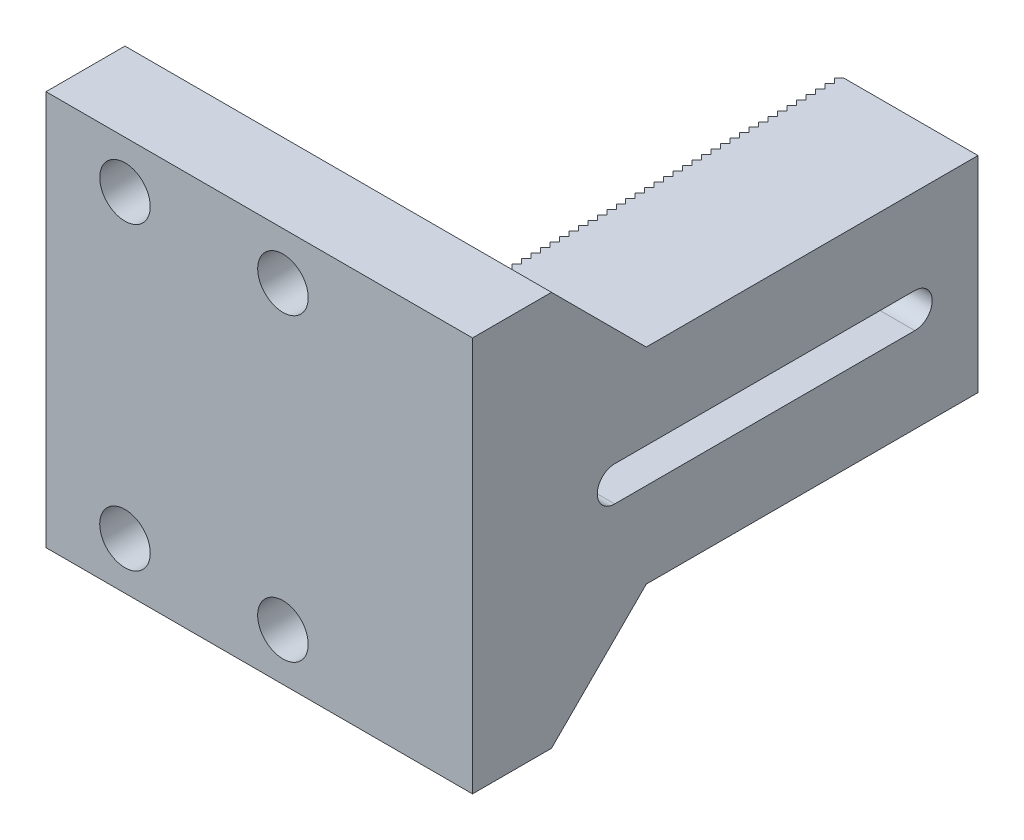
SolidWorks part; units mm, degrees
ref_plane "前视基准面" through (0, 0, 0) normal (0, 0, 1) x (1, 0, 0)
ref_plane "上视基准面" through (0, 0, 0) normal (0, 1, 0) x (1, 0, 0)
ref_plane "右视基准面" through (0, 0, 0) normal (1, 0, 0) x (0, 0, -1)
sketch "草图1" plane through (0, 0, 0) normal (0, 1, 0) x (1, 0, 0)
  line L0 (0, 0) -> (-27, 0)
  line L1 (-27, 0) -> (-27, 5)
  line L2 (-27, 5) -> (-8, 5)
  line L3 (-8, 5) -> (-8, 32)
  line L4 (-8, 32) -> (0, 32)
  line L5 (0, 32) -> (0, 0)
  dimension "D1" = 5
  dimension "D2" = 8
  dimension "D3" = 27
  dimension "D4" = 32
extrude "凸台-拉伸1" add sketch "草图1" along normal blind 25
sketch "草图4" plane through (0, 0, 0) normal (0, 0, 1) x (1, 0, 0)
  line L0 (-27, 25) -> (-8, 25) construction
  line L1 (-17, 27.5741) -> (-17, -6.7865) construction
  line L2 (-27, 12.5) -> (-8.9406, 12.5) construction
  line L3 (-27, 25) -> (-27, 0) construction
  line L5 (-8, 25) -> (-8, 0) construction
  circle A0 centre (-22, 22) radius 1.6
  circle A1 centre (-12, 22) radius 1.6
  circle A2 centre (-22, 3) radius 1.6
  circle A3 centre (-12, 3) radius 1.6
  dimension "D1" = 3.2
  dimension "D2" = 10
  dimension "D3" = 19
  dimension "D5" = 4
  dimension "D4" = 10
extrude "切除-拉伸2" cut sketch "草图4" along direction (0, 0, 1) on the side against the normal through all
sketch "草图8" plane through (-8, 0, 0) normal (-1, 0, 0) x (0, 0, 1)
  line L0 (-32, 19) -> (-11, 19)
  line L1 (-32, 25) -> (-32, 0) construction
  line L2 (-11, 19) -> (-5, 25)
  line L3 (-5, 25) -> (-32, 25)
  line L4 (-32, 25) -> (-32, 19)
  line L5 (-32, 12.5) -> (0.3903, 12.5) construction
  line L6 (-11, 6) -> (-5, 0)
  line L7 (-5, 0) -> (-32, 0)
  line L8 (-32, 0) -> (-32, 6)
  line L9 (-32, 6) -> (-11, 6)
  line L10 (-5, 25) -> (-5, 0) construction
  dimension "D1" = 45
  dimension "D2" = 13
extrude "切除-拉伸5" cut sketch "草图8" against normal through all
sketch "草图11" plane through (0, 6, 0) normal (0, -1, 0) x (1, 0, 0)
  line L0 (-8, -5) -> (-8, -32)
  line L1 (-8, -32) -> (-8.5, -32)
  line L2 (-8.5, -32) -> (-8.8, -31.7)
  line L3 (-8.8, -31.7) -> (-8.5, -31.4)
  line L29 (-8, -5) -> (-27, -5) construction
  line L30 (-8.5, -5) -> (-8, -5)
  line L31 (-8.5, -31.4) -> (-8.8, -31.1)
  line L32 (-8.8, -31.1) -> (-8.5, -30.8)
  line L33 (-8.5, -30.8) -> (-8.8, -30.5)
  line L34 (-8.8, -30.5) -> (-8.5, -30.2)
  line L35 (-8.5, -30.2) -> (-8.8, -29.9)
  line L36 (-8.8, -29.9) -> (-8.5, -29.6)
  line L37 (-8.5, -29.6) -> (-8.8, -29.3)
  line L38 (-8.8, -29.3) -> (-8.5, -29)
  line L39 (-8.5, -29) -> (-8.8, -28.7)
  line L40 (-8.8, -28.7) -> (-8.5, -28.4)
  line L41 (-8.5, -28.4) -> (-8.8, -28.1)
  line L42 (-8.8, -28.1) -> (-8.5, -27.8)
  line L43 (-8.5, -27.8) -> (-8.8, -27.5)
  line L44 (-8.8, -27.5) -> (-8.5, -27.2)
  line L45 (-8.5, -27.2) -> (-8.8, -26.9)
  line L46 (-8.8, -26.9) -> (-8.5, -26.6)
  line L47 (-8.5, -26.6) -> (-8.8, -26.3)
  line L48 (-8.8, -26.3) -> (-8.5, -26)
  line L49 (-8.5, -26) -> (-8.8, -25.7)
  line L50 (-8.8, -25.7) -> (-8.5, -25.4)
  line L51 (-8.5, -25.4) -> (-8.8, -25.1)
  line L52 (-8.8, -25.1) -> (-8.5, -24.8)
  line L53 (-8.5, -24.8) -> (-8.8, -24.5)
  line L54 (-8.8, -24.5) -> (-8.5, -24.2)
  line L55 (-8.5, -24.2) -> (-8.8, -23.9)
  line L56 (-8.8, -23.9) -> (-8.5, -23.6)
  line L57 (-8.5, -23.6) -> (-8.8, -23.3)
  line L58 (-8.8, -23.3) -> (-8.5, -23)
  line L59 (-8.5, -23) -> (-8.8, -22.7)
  line L60 (-8.8, -22.7) -> (-8.5, -22.4)
  line L61 (-8.5, -22.4) -> (-8.8, -22.1)
  line L62 (-8.8, -22.1) -> (-8.5, -21.8)
  line L63 (-8.5, -21.8) -> (-8.8, -21.5)
  line L64 (-8.8, -21.5) -> (-8.5, -21.2)
  line L65 (-8.5, -21.2) -> (-8.8, -20.9)
  line L66 (-8.8, -20.9) -> (-8.5, -20.6)
  line L67 (-8.5, -20.6) -> (-8.8, -20.3)
  line L68 (-8.8, -20.3) -> (-8.5, -20)
  line L69 (-8.5, -20) -> (-8.8, -19.7)
  line L70 (-8.8, -19.7) -> (-8.5, -19.4)
  line L71 (-8.5, -19.4) -> (-8.8, -19.1)
  line L72 (-8.8, -19.1) -> (-8.5, -18.8)
  line L73 (-8.5, -18.8) -> (-8.8, -18.5)
  line L74 (-8.8, -18.5) -> (-8.5, -18.2)
  line L75 (-8.5, -18.2) -> (-8.8, -17.9)
  line L76 (-8.8, -17.9) -> (-8.5, -17.6)
  line L77 (-8.5, -17.6) -> (-8.8, -17.3)
  line L78 (-8.8, -17.3) -> (-8.5, -17)
  line L79 (-8.5, -17) -> (-8.8, -16.7)
  line L80 (-8.8, -16.7) -> (-8.5, -16.4)
  line L81 (-8.5, -16.4) -> (-8.8, -16.1)
  line L82 (-8.8, -16.1) -> (-8.5, -15.8)
  line L83 (-8.5, -15.8) -> (-8.8, -15.5)
  line L84 (-8.8, -15.5) -> (-8.5, -15.2)
  line L85 (-8.5, -15.2) -> (-8.8, -14.9)
  line L86 (-8.8, -14.9) -> (-8.5, -14.6)
  line L87 (-8.5, -14.6) -> (-8.8, -14.3)
  line L88 (-8.8, -14.3) -> (-8.5, -14)
  line L89 (-8.5, -14) -> (-8.8, -13.7)
  line L90 (-8.8, -13.7) -> (-8.5, -13.4)
  line L91 (-8.5, -13.4) -> (-8.8, -13.1)
  line L92 (-8.8, -13.1) -> (-8.5, -12.8)
  line L93 (-8.5, -12.8) -> (-8.8, -12.5)
  line L94 (-8.8, -12.5) -> (-8.5, -12.2)
  line L95 (-8.5, -12.2) -> (-8.8, -11.9)
  line L96 (-8.8, -11.9) -> (-8.5, -11.6)
  line L97 (-8.5, -11.6) -> (-8.8, -11.3)
  line L98 (-8.8, -11.3) -> (-8.5, -11)
  line L99 (-8.5, -11) -> (-8.8, -10.7)
  line L100 (-8.8, -10.7) -> (-8.5, -10.4)
  line L101 (-8.5, -10.4) -> (-8.8, -10.1)
  line L102 (-8.8, -10.1) -> (-8.5, -9.8)
  line L103 (-8.5, -9.8) -> (-8.8, -9.5)
  line L104 (-8.8, -9.5) -> (-8.5, -9.2)
  line L105 (-8.5, -9.2) -> (-8.8, -8.9)
  line L106 (-8.8, -8.9) -> (-8.5, -8.6)
  line L107 (-8.5, -8.6) -> (-8.8, -8.3)
  line L108 (-8.8, -8.3) -> (-8.5, -8)
  line L109 (-8.5, -8) -> (-8.8, -7.7)
  line L110 (-8.8, -7.7) -> (-8.5, -7.4)
  line L111 (-8.5, -7.4) -> (-8.8, -7.1)
  line L112 (-8.8, -7.1) -> (-8.5, -6.8)
  line L113 (-8.5, -6.8) -> (-8.8, -6.5)
  line L114 (-8.8, -6.5) -> (-8.5, -6.2)
  line L115 (-8.5, -6.2) -> (-8.5, -5)
  dimension "D1" = 0.5
  dimension "D2" = 135
  dimension "D3" = 0.6
extrude "凸台-拉伸2" add sketch "草图11" against normal up to surface (13 mm away) up to face at (-4, 19, -21.5)
sketch "草图6" plane through (-8, 0, 0) normal (-1, 0, 0) x (0, 0, 1)
  line L0 (-39, 12.5) -> (-12.5869, 12.5) construction
  line L2 (-32, 25) -> (-5, 25) construction
  line L3 (-32, 0) -> (-5, 0) construction
  line L4 (-28, 12.5) -> (-9, 12.5) construction
  line L5 (-28, 13.6) -> (-9, 13.6)
  line L6 (-28, 11.4) -> (-9, 11.4)
  line L7 (-32, 25) -> (-32, 0) construction
  arc A2 (-28, 13.6) -> (-28, 11.4) centre (-28, 12.5) ccw
  arc A3 (-9, 11.4) -> (-9, 13.6) centre (-9, 12.5) ccw
  point P4 (-18.5, 12.5)
  dimension "D1" = 4
  dimension "D2" = 1.1
  dimension "D3" = 19
extrude "切除-拉伸4" cut sketch "草图6" against normal through all and the other way blind 10
